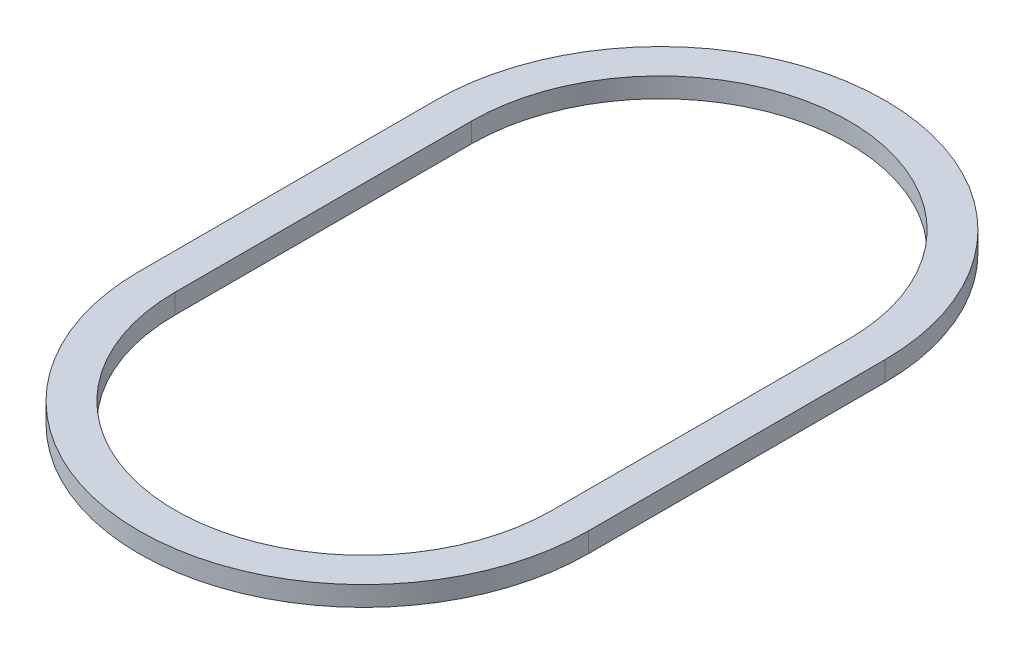
SolidWorks part; units mm, degrees
ref_plane "前视基准面" through (0, 0, 0) normal (0, 0, 1) x (1, 0, 0)
ref_plane "上视基准面" through (0, 0, 0) normal (0, 1, 0) x (1, 0, 0)
ref_plane "右视基准面" through (0, 0, 0) normal (1, 0, 0) x (0, 0, -1)
sketch "草图1" plane through (0, 0, 0) normal (0, 1, 0) x (1, 0, 0)
  line L0 (0, 0) -> (0, -33) construction
  line L1 (0, -33) -> (0, 0) construction
  line L2 (25, 0) -> (25, -33)
  line L3 (-25, 0) -> (-25, -33)
  line L4 (-21, -33) -> (-21, 0)
  line L5 (21, -33) -> (21, 0)
  arc A0 (25, 0) -> (-25, 0) centre (0, 0) ccw
  arc A1 (-25, -33) -> (25, -33) centre (0, -33) ccw
  arc A2 (-21, -33) -> (21, -33) centre (0, -33) ccw
  arc A3 (21, 0) -> (-21, 0) centre (0, 0) ccw
  point P5 (0, -16.5)
  point P10 (0, -16.5)
  dimension "D1" = 25
  dimension "D3" = 21
  dimension "D2" = 33
extrude "凸台-拉伸1" add sketch "草图1" along normal blind 2.2
